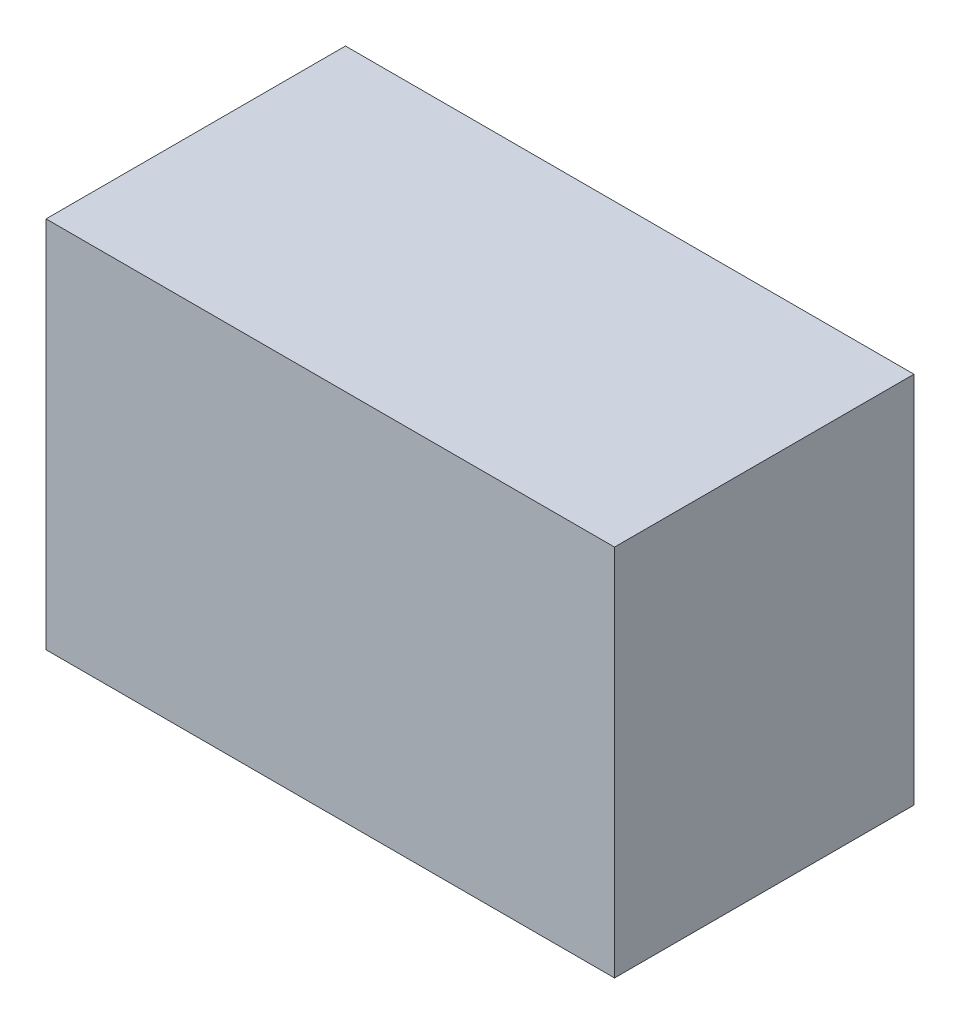
SolidWorks part; units mm, degrees
ref_plane "Front Plane" through (0, 0, 0) normal (0, 0, 1) x (1, 0, 0)
ref_plane "Top Plane" through (0, 0, 0) normal (0, 1, 0) x (1, 0, 0)
ref_plane "Right Plane" through (0, 0, 0) normal (1, 0, 0) x (0, 0, -1)
sketch "Sketch1" plane through (0, 0, 0) normal (0, 1, 0) x (1, 0, 0)
  line L1 (-166.37, 87.63) -> (166.37, 87.63)
  line L2 (-166.37, 87.63) -> (-166.37, -87.63)
  line L3 (-166.37, -87.63) -> (166.37, -87.63)
  line L4 (166.37, 87.63) -> (166.37, -87.63)
  line L5 (-166.37, 87.63) -> (166.37, -87.63) construction
  line L6 (-166.37, -87.63) -> (166.37, 87.63) construction
  point P0 (0, 0)
  dimension "D1" = 332.74
  dimension "D2" = 175.26
extrude "Boss-Extrude1" add sketch "Sketch1" along normal blind 218.44
